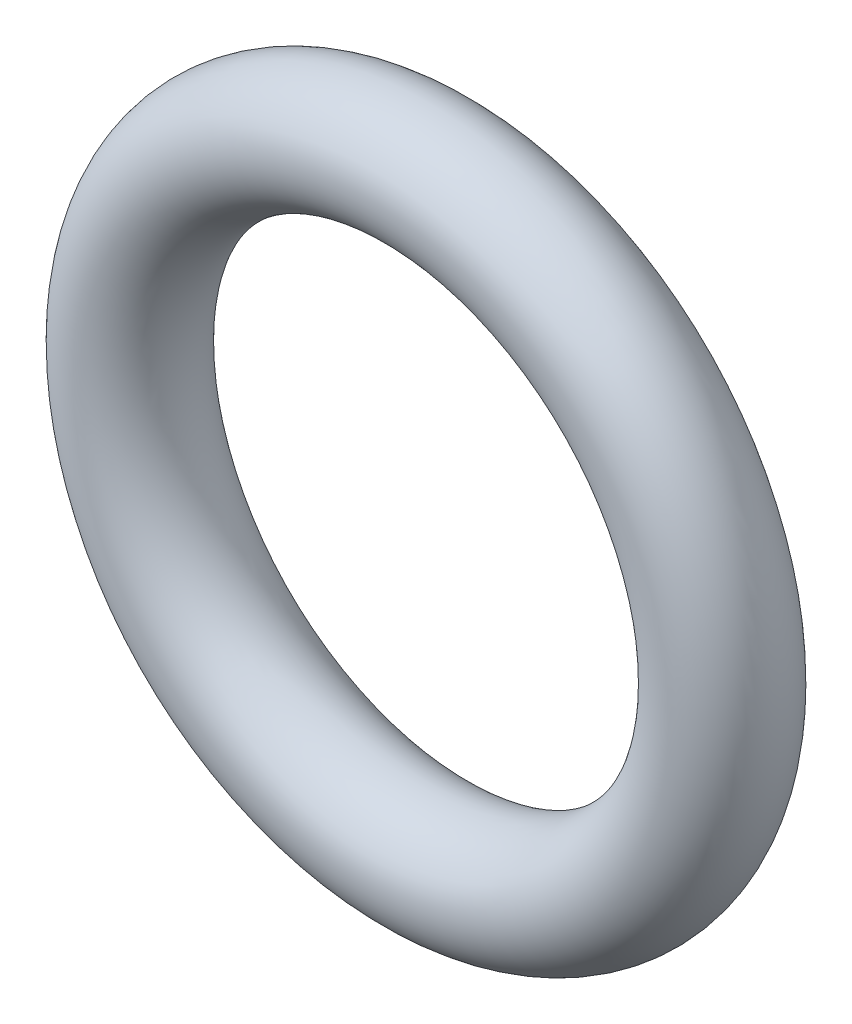
SolidWorks part; units mm, degrees
material "Rubber"
ref_plane "Front" through (0, 0, 0) normal (0, 0, 1) x (1, 0, 0)
ref_plane "Top" through (0, 0, 0) normal (0, 1, 0) x (1, 0, 0)
ref_plane "Right" through (0, 0, 0) normal (1, 0, 0) x (0, 0, -1)
sketch "Sketch1" plane through (0, 0, 0) normal (1, 0, 0) x (0, -1, 0)
  line L0 (0, -1) -> (0, 1) construction
  line L2 (-6.6, 0) -> (6.6, 0) construction
  line L3 (-4, 0) -> (4, 0) construction
  circle A0 centre (5, 0) radius 1
  point P9 (4, 0)
  point P10 (6, 0)
  point P13 (5, 1)
  point P14 (5, -1)
  dimension "Width" = 2
  dimension "ID" = 8
revolve "Revolve1" add sketch "Sketch1" angle 360 about L0
